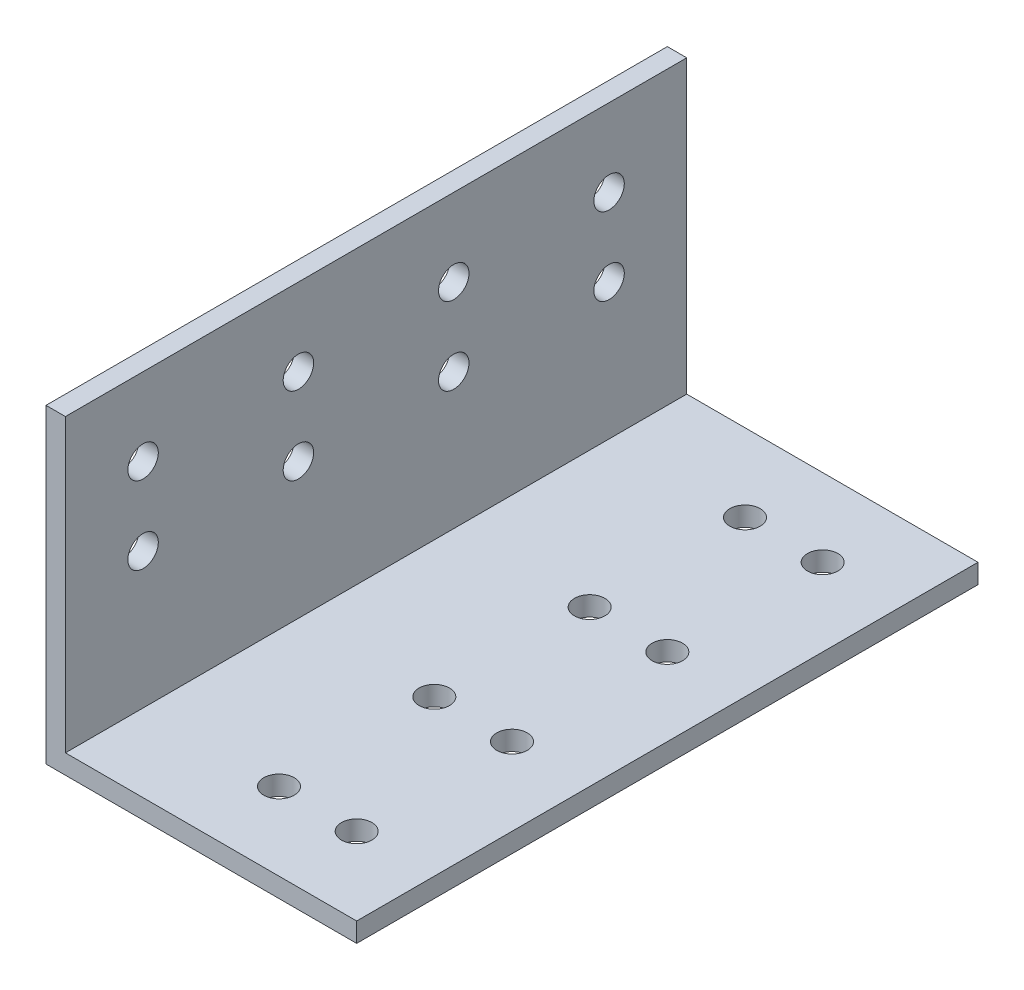
SolidWorks part; units mm, degrees
material "6061-T6 (SS)"
ref_plane "Front Plane" through (0, 0, 0) normal (0, 0, 1) x (1, 0, 0)
ref_plane "Top Plane" through (0, 0, 0) normal (0, 1, 0) x (1, 0, 0)
ref_plane "Right Plane" through (0, 0, 0) normal (1, 0, 0) x (0, 0, -1)
sketch "Sketch2" plane through (0, 0, 0) normal (0, 0, 1) x (1, 0, 0)
  line L0 (0, 0) -> (0, 50.8)
  line L1 (0, 50.8) -> (3.175, 50.8)
  line L2 (3.175, 50.8) -> (3.175, 3.175)
  line L3 (3.175, 3.175) -> (50.8, 3.175)
  line L4 (50.8, 3.175) -> (50.8, 0)
  line L5 (50.8, 0) -> (0, 0)
  dimension "D1" = 3.175
  dimension "D2" = 50.8
  dimension "D3" = 50.8
extrude "Boss-Extrude1" add sketch "Sketch2" along normal blind 101.6 contours L2 L3 L4 L5 L0 L1
sketch "Sketch3" plane through (0, 3.175, 0) normal (0, 1, 0) x (1, 0, 0)
  line L0 (3.175, -101.6) -> (3.175, 0) construction
  line L1 (3.175, 0) -> (50.8, 0) construction
  circle A0 centre (25.4, -12.7) radius 2.4892
  circle A1 centre (38.1, -12.7) radius 2.4892
  circle A2 centre (38.1, -38.1) radius 2.4892
  circle A3 centre (38.1, -63.5) radius 2.4892
  circle A4 centre (38.1, -88.9) radius 2.4892
  circle A5 centre (25.4, -38.1) radius 2.4892
  circle A6 centre (25.4, -63.5) radius 2.4892
  circle A7 centre (25.4, -88.9) radius 2.4892
  dimension "D3" = 12.7
  dimension "D4" = 25.4
  dimension "D5" = 22.225
  dimension "D6" = 4.9784
  dimension "D7" = 12.7
  dimension "D1" = 2
  dimension "D2" = 4
extrude "Cut-Extrude1" cut sketch "Sketch3" against normal through all
sketch "Sketch4" plane through (3.175, 0, 0) normal (1, 0, 0) x (0, 0, -1)
  line L0 (0, 50.8) -> (0, 3.175) construction
  line L1 (-101.6, 3.175) -> (0, 3.175) construction
  circle A0 centre (-12.7, 25.4) radius 2.4892
  circle A1 centre (-38.1, 25.4) radius 2.4892
  circle A2 centre (-63.5, 25.4) radius 2.4892
  circle A3 centre (-88.9, 25.4) radius 2.4892
  circle A4 centre (-38.1, 38.1) radius 2.4892
  circle A5 centre (-63.5, 38.1) radius 2.4892
  circle A6 centre (-88.9, 38.1) radius 2.4892
  circle A7 centre (-12.7, 38.1) radius 2.4892
  dimension "D3" = 12.7
  dimension "D4" = 12.7
  dimension "D5" = 25.4
  dimension "D6" = 22.225
  dimension "D7" = 4.9784
  dimension "D1" = 4
  dimension "D2" = 2
extrude "Cut-Extrude2" cut sketch "Sketch4" against normal through all
